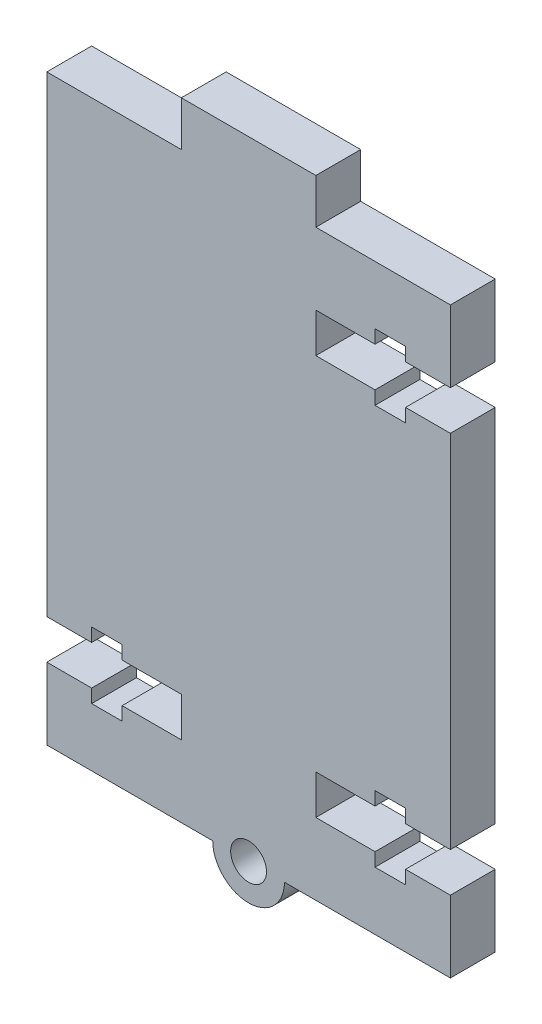
SolidWorks part; units mm, degrees
ref_plane "Front Plane" through (0, 0, 0) normal (0, 0, 1) x (1, 0, 0)
ref_plane "Top Plane" through (0, 0, 0) normal (0, 1, 0) x (1, 0, 0)
ref_plane "Right Plane" through (0, 0, 0) normal (1, 0, 0) x (0, 0, -1)
sketch "Sketch1" plane through (0, 0, 0) normal (0, 0, 1) x (1, 0, 0)
  line L0 (7.5, 32.5) -> (7.5, 37.5)
  line L1 (-22.5, 32.5) -> (-7.5, 32.5)
  line L2 (-22.5, 32.5) -> (-22.5, -32.5)
  line L3 (-22.5, -32.5) -> (22.5, -32.5)
  line L4 (22.5, 32.5) -> (22.5, -32.5)
  line L5 (7.5, 37.5) -> (-7.5, 37.5)
  line L6 (-7.5, 37.5) -> (-7.5, 32.5)
  line L7 (7.5, 32.5) -> (22.5, 32.5)
  dimension "D1" = 45
  dimension "D2" = 65
  dimension "D3" = 22.5
  dimension "D4" = 32.5
  dimension "D5" = 15
  dimension "D6" = 15
  dimension "D7" = 5
extrude "Boss-Extrude1" add sketch "Sketch1" along normal blind 5
sketch "Sketch3" plane through (0, 0, 5) normal (0, 0, 1) x (1, 0, 0)
  line L0 (0, 0) -> (28.1265, 0) construction
  line L13 (22.5, -32.5) -> (22.5, 32.5) construction
  line L14 (22.5, 24.5) -> (17.5, 24.5)
  line L15 (17.5, 24.5) -> (17.5, 26)
  line L16 (17.5, 26) -> (14.1, 26)
  line L17 (14.1, 26) -> (14.1, 24.5)
  line L18 (14.1, 24.5) -> (7.5, 24.5)
  line L19 (7.5, 24.5) -> (7.5, 20.1)
  line L20 (7.5, 20.1) -> (14.1, 20.1)
  line L21 (14.1, 20.1) -> (14.1, 18.6)
  line L22 (14.1, 18.6) -> (17.5, 18.6)
  line L23 (17.5, 18.6) -> (17.5, 20.1)
  line L24 (17.5, 20.1) -> (22.5, 20.1)
  line L25 (22.5, 24.5) -> (22.5, 20.1)
  line L26 (-7.5, 32.5) -> (-22.5, 32.5) construction
  line L27 (0, 0) -> (0, 42.4523) construction
  line L28 (22.5, -24.5) -> (22.5, -20.1)
  line L29 (17.5, -20.1) -> (22.5, -20.1)
  line L30 (17.5, -18.6) -> (17.5, -20.1)
  line L31 (14.1, -18.6) -> (17.5, -18.6)
  line L32 (14.1, -20.1) -> (14.1, -18.6)
  line L33 (7.5, -20.1) -> (14.1, -20.1)
  line L34 (7.5, -24.5) -> (7.5, -20.1)
  line L35 (14.1, -24.5) -> (7.5, -24.5)
  line L36 (14.1, -26) -> (14.1, -24.5)
  line L37 (17.5, -26) -> (14.1, -26)
  line L38 (17.5, -24.5) -> (17.5, -26)
  line L39 (22.5, -24.5) -> (17.5, -24.5)
  line L40 (-22.5, -24.5) -> (-17.5, -24.5)
  line L41 (-17.5, -24.5) -> (-17.5, -26)
  line L42 (-17.5, -26) -> (-14.1, -26)
  line L43 (-14.1, -26) -> (-14.1, -24.5)
  line L44 (-14.1, -24.5) -> (-7.5, -24.5)
  line L45 (-7.5, -24.5) -> (-7.5, -20.1)
  line L46 (-7.5, -20.1) -> (-14.1, -20.1)
  line L47 (-14.1, -20.1) -> (-14.1, -18.6)
  line L48 (-14.1, -18.6) -> (-17.5, -18.6)
  line L49 (-17.5, -18.6) -> (-17.5, -20.1)
  line L50 (-17.5, -20.1) -> (-22.5, -20.1)
  line L51 (-22.5, -24.5) -> (-22.5, -20.1)
  dimension "D8" = 4.4
  dimension "D9" = 1.5
  dimension "D10" = 1.5
  dimension "D11" = 3.4
  dimension "D12" = 5
  dimension "D13" = 8
  dimension "D14" = 15
extrude "Cut-Extrude1" cut sketch "Sketch3" against normal blind 5
sketch "Sketch5" plane through (0, 0, 5) normal (0, 0, 1) x (1, 0, 0)
  line L0 (0, 0) -> (0, -42.6845) construction
  line L1 (-22.5, -32.5) -> (22.5, -32.5) construction
  circle A0 centre (0, -32.5) radius 2
  circle A1 centre (0, -32.5) radius 4
  dimension "D1" = 4
  dimension "D2" = 8
extrude "Boss-Extrude2" add sketch "Sketch5" against normal blind 5
sketch "Sketch6" plane through (0, 0, 5) normal (0, 0, 1) x (1, 0, 0)
  line L0 (-2, -32.5) -> (2, -32.5) construction
  circle A0 centre (0, -32.5) radius 2
  dimension "D1" = 4
extrude "Cut-Extrude2" cut sketch "Sketch6" against normal blind 5
